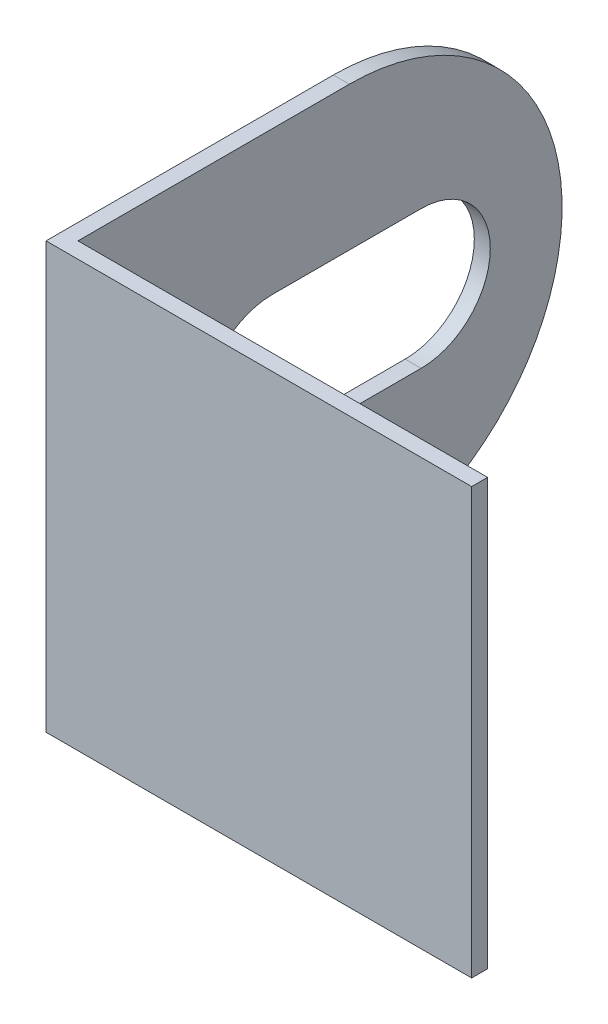
SolidWorks part; units mm, degrees
ref_plane "Front Plane" through (0, 0, 0) normal (0, 0, 1) x (1, 0, 0)
ref_plane "Top Plane" through (0, 0, 0) normal (0, 1, 0) x (1, 0, 0)
ref_plane "Right Plane" through (0, 0, 0) normal (1, 0, 0) x (0, 0, -1)
sketch "Sketch1" plane through (0, 0, 0) normal (0, 1, 0) x (1, 0, 0)
  line L0 (-18.5, 23.5) -> (-18.5, -22)
  line L1 (-18.5, -22) -> (20, -22)
  line L2 (20, -22) -> (20, -23.5)
  line L3 (20, -23.5) -> (-20, -23.5)
  line L4 (-20, -23.5) -> (-20, 23.5)
  line L5 (-20, 23.5) -> (-18.5, 23.5)
  line L6 (-20, 23.5) -> (20, -23.5) construction
  point P6 (-2.8127, -2.24)
  dimension "D1" = 1.5
  dimension "D2" = 47
  dimension "D3" = 40
extrude "Boss-Extrude1" add sketch "Sketch1" along normal blind 40
sketch "Sketch2" plane through (-20, 0, 0) normal (-1, 0, 0) x (0, 0, 1)
  line L0 (-23.5, 40) -> (-23.5, 0) construction
  line L1 (-23.5, 0) -> (23.5, 0) construction
  line L3 (-23.5, 20) -> (-16.75, 20) construction
  line L4 (-10.25, 20) -> (3.75, 20) construction
  line L5 (-10.25, 26.5) -> (3.75, 26.5)
  line L6 (-10.25, 13.5) -> (3.75, 13.5)
  line L7 (-3.5, 0) -> (-23.5, 0)
  line L8 (-23.5, 0) -> (-23.5, 40)
  line L9 (-23.5, 40) -> (-3.5, 40)
  arc A0 (-3.5, 40) -> (-3.5, 0) centre (-3.5, 20) ccw
  arc A1 (-10.25, 26.5) -> (-10.25, 13.5) centre (-10.25, 20) ccw
  arc A2 (3.75, 13.5) -> (3.75, 26.5) centre (3.75, 20) ccw
  point P1 (5.9556, 37.6236)
  point P10 (-3.25, 20)
  point P16 (10.25, 20)
  point P21 (-3.5, 40)
  point P25 (7.7993, 40)
  line M9 (-23.5, 0) -> (23.5, 0)
  line M11 (23.5, 40) -> (-23.5, 40)
  line M12 (-23.5, 40) -> (-23.5, 0)
  dimension "D1" = 40
  dimension "D2" = 6.75
  dimension "D3" = 27
  dimension "D4" = 13
extrude "Cut-Extrude1" cut sketch "Sketch2" against normal blind 40 contours A0 L8 M9 | A0 M11 M12 | L6 A2 L5 A1
